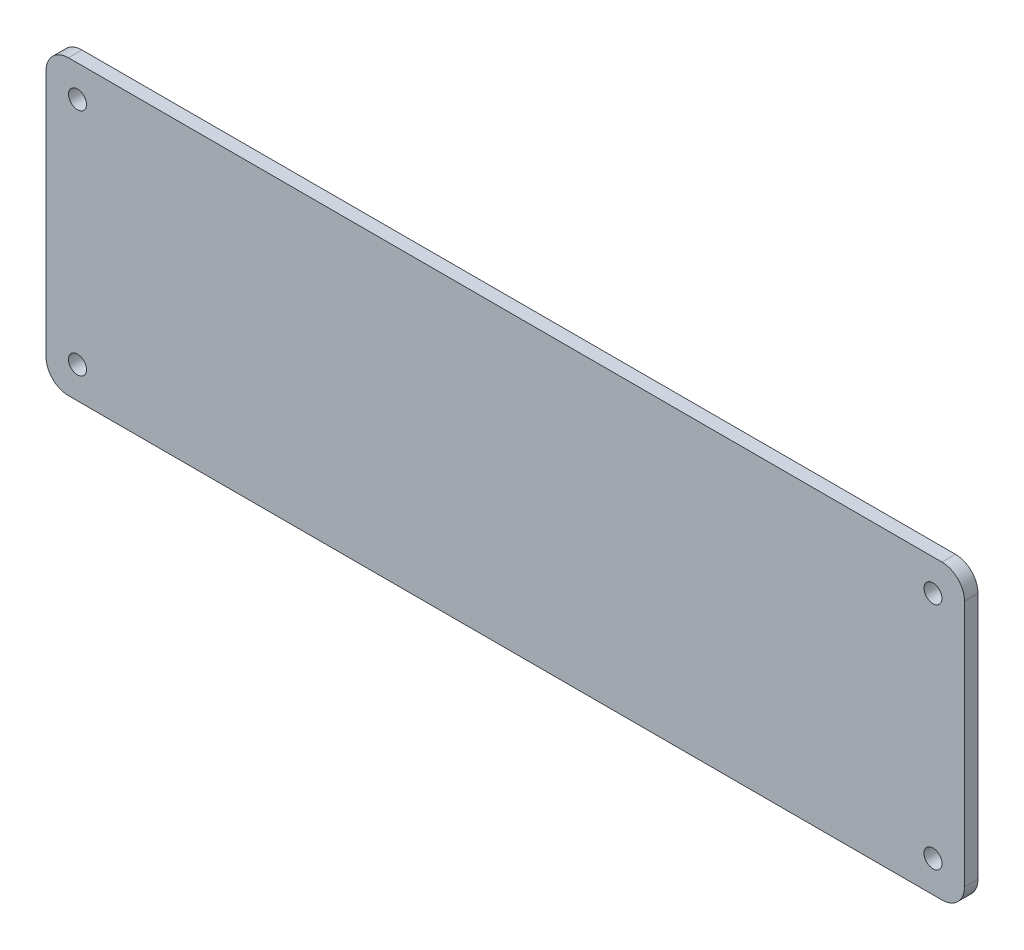
SolidWorks part; units mm, degrees
ref_plane "Front Plane" through (0, 0, 0) normal (0, 0, 1) x (1, 0, 0)
ref_plane "Top Plane" through (0, 0, 0) normal (0, 1, 0) x (1, 0, 0)
ref_plane "Right Plane" through (0, 0, 0) normal (1, 0, 0) x (0, 0, -1)
sketch "Sketch1" plane through (0, 0, 0) normal (0, 0, 1) x (1, 0, 0)
  line L1 (-102, 32.5) -> (102, 32.5)
  line L2 (-102, 32.5) -> (-102, -32.5)
  line L3 (-102, -32.5) -> (102, -32.5)
  line L4 (102, 32.5) -> (102, -32.5)
  line L5 (-102, 32.5) -> (102, -32.5) construction
  line L6 (-102, -32.5) -> (102, 32.5) construction
  line L7 (-77.5, 26) -> (77.5, 26) construction
  line L8 (-77.5, 26) -> (-77.5, -26) construction
  line L9 (-77.5, -26) -> (77.5, -26) construction
  line L10 (77.5, 26) -> (77.5, -26) construction
  line L11 (-77.5, 26) -> (77.5, -26) construction
  line L12 (-77.5, -26) -> (77.5, 26) construction
  line L13 (-95, 25.5) -> (95, 25.5) construction
  line L14 (-95, 25.5) -> (-95, -25.5) construction
  line L15 (-95, -25.5) -> (95, -25.5) construction
  line L16 (95, 25.5) -> (95, -25.5) construction
  line L17 (-95, 25.5) -> (95, -25.5) construction
  line L18 (-95, -25.5) -> (95, 25.5) construction
  circle A0 centre (95, -25.5) radius 2
  circle A1 centre (95, 25.5) radius 2
  circle A2 centre (-95, 25.5) radius 2
  circle A3 centre (-95, -25.5) radius 2
  point P0 (0, 0)
  point P6 (0, 0)
  point P11 (0, 0)
  dimension "D5" = 4
  dimension "D6" = 5
  dimension "D7" = 5
  dimension "D1" = 155
  dimension "D2" = 190
  dimension "D3" = 52
  dimension "D4" = 65
extrude "Boss-Extrude1" add sketch "Sketch1" along normal mid plane 3
fillet "Fillet1" radius 5 4 edges at (-102, 32.5, 0) (-102, -32.5, 0) (102, -32.5, 0) (102, 32.5, 0)
